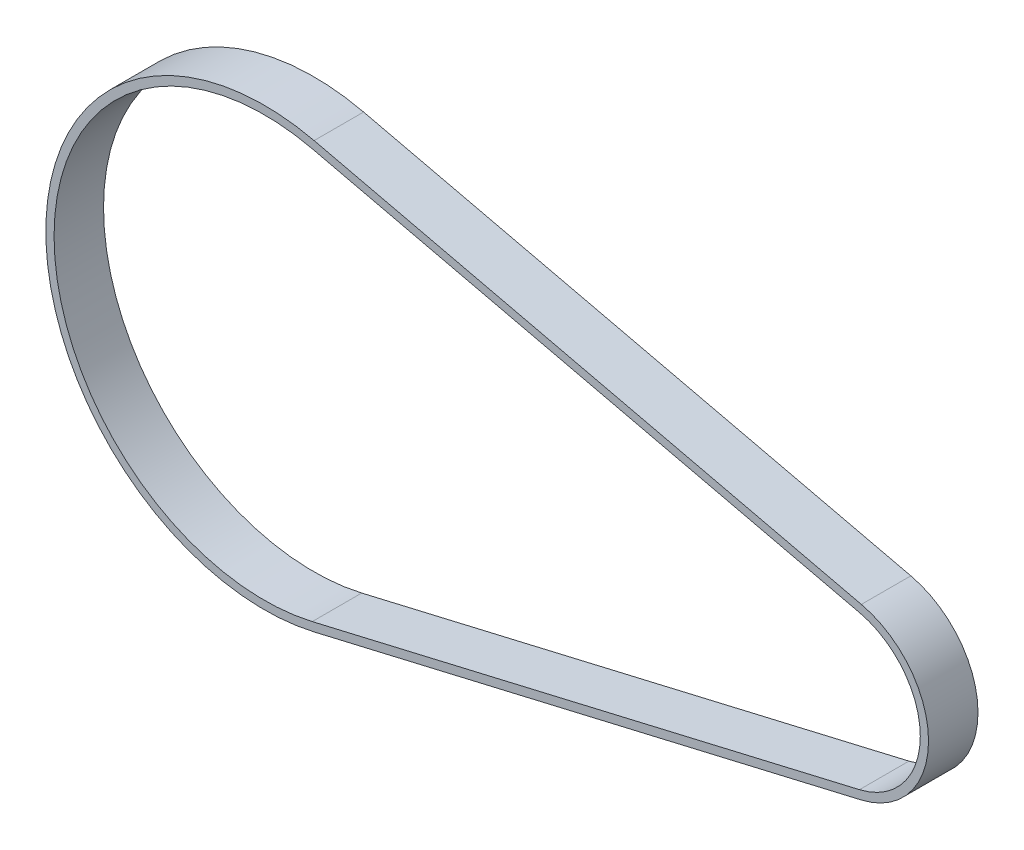
SolidWorks part; units mm, degrees
material "Rubber"
ref_plane "Front Plane" through (0, 0, 0) normal (0, 0, 1) x (1, 0, 0)
ref_plane "Top Plane" through (0, 0, 0) normal (0, 1, 0) x (1, 0, 0)
ref_plane "Right Plane" through (0, 0, 0) normal (1, 0, 0) x (0, 0, -1)
sketch "Sketch1" plane through (0, 0, 0) normal (0, 0, 1) x (1, 0, 0)
  line L0 (5.8104, 24.8292) -> (72.176, 9.2988)
  line L1 (0, 0) -> (70, 0) construction
  line L2 (72.176, -9.2988) -> (5.8104, -24.8292)
  line L3 (6.0382, 25.8029) -> (72.4039, 10.2725)
  line L4 (72.4039, -10.2725) -> (6.0382, -25.8029)
  arc A0 (5.8104, 24.8292) -> (5.8104, -24.8292) centre (0, 0) ccw
  arc A1 (72.176, -9.2988) -> (72.176, 9.2988) centre (70, 0) ccw
  arc A2 (72.4039, -10.2725) -> (72.4039, 10.2725) centre (70, 0) ccw
  arc A3 (6.0382, 25.8029) -> (6.0382, -25.8029) centre (0, 0) ccw
  circle A4 centre (0, 0) radius 50.8 construction
  circle A5 centre (70, 0) radius 15 construction
  dimension "D1" = 25.5
  dimension "D2" = 9.55
  dimension "D5" = 101.6
  dimension "D6" = 30
  dimension "D3" = 70
  dimension "D4" = 1
extrude "Boss-Extrude1" add sketch "Sketch1" along normal blind 6
